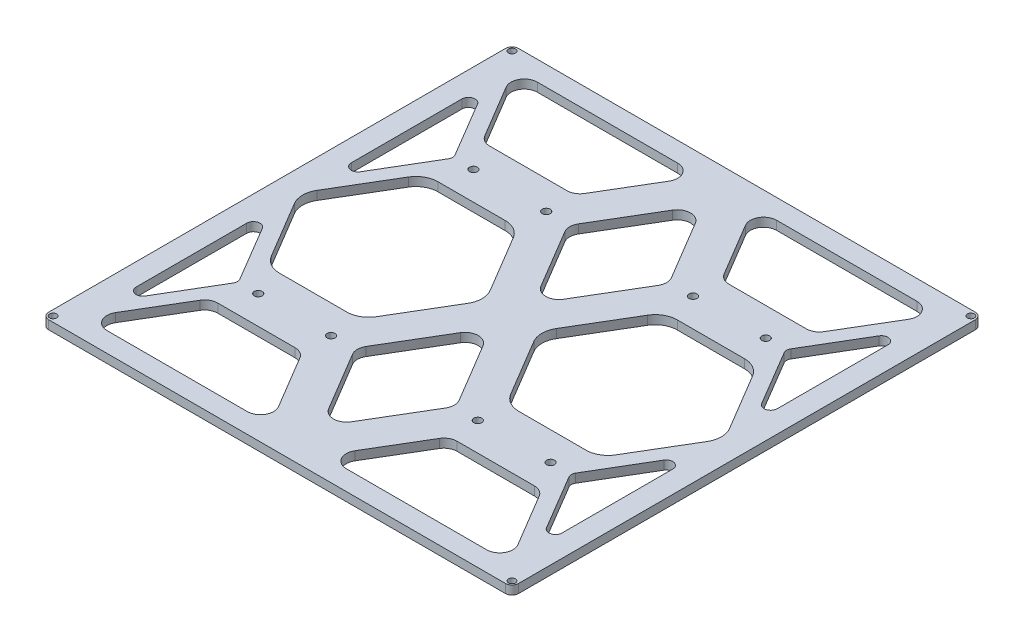
SolidWorks part; units mm, degrees
ref_plane "정면" through (0, 0, 0) normal (0, 0, 1) x (1, 0, 0)
ref_plane "윗면" through (0, 0, 0) normal (0, 1, 0) x (1, 0, 0)
ref_plane "우측면" through (0, 0, 0) normal (1, 0, 0) x (0, 0, -1)
sketch "스케치1" plane through (0, 0, 0) normal (0, 1, 0) x (1, 0, 0)
  line L1 (-107, -107) -> (107, -107)
  line L2 (-107, -107) -> (-107, 107)
  line L3 (-107, 107) -> (107, 107)
  line L4 (107, -107) -> (107, 107)
  line L5 (-107, -107) -> (107, 107) construction
  line L6 (-107, 107) -> (107, -107) construction
  point P0 (0, 0)
  dimension "D1" = 214
extrude "보스-돌출1" add sketch "스케치1" along normal blind 4
fillet "필렛1" radius 3 4 edges at (107, 2, -107) (107, 2, 107) (-107, 2, 107) (-107, 2, -107)
sketch "스케치2" plane through (0, 4, 0) normal (0, 1, 0) x (1, 0, 0)
  line L0 (0, 104.5) -> (0, -104.5) construction
  line L1 (-104.5, -104.5) -> (104.5, -104.5) construction
  line L2 (-104.5, -104.5) -> (-104.5, 104.5) construction
  line L3 (-104.5, 104.5) -> (104.5, 104.5) construction
  line L4 (104.5, -104.5) -> (104.5, 104.5) construction
  line L5 (-104.5, -104.5) -> (104.5, 104.5) construction
  line L6 (-104.5, 104.5) -> (104.5, -104.5) construction
  line L7 (33.425, -49) -> (-33.425, -49) construction
  line L8 (33.425, -49) -> (33.425, 49) construction
  line L9 (33.425, 49) -> (-33.425, 49) construction
  line L10 (-33.425, -49) -> (-33.425, 49) construction
  line L11 (33.425, -49) -> (-33.425, 49) construction
  line L12 (33.425, 49) -> (-33.425, -49) construction
  line L13 (-66.575, -49) -> (66.575, -49) construction
  line L14 (-66.575, -49) -> (-66.575, 49) construction
  line L15 (-66.575, 49) -> (66.575, 49) construction
  line L16 (66.575, -49) -> (66.575, 49) construction
  line L17 (-66.575, -49) -> (66.575, 49) construction
  line L18 (-66.575, 49) -> (66.575, -49) construction
  circle A0 centre (-104.5, 104.5) radius 1.6
  circle A1 centre (104.5, -104.5) radius 1.6
  circle A2 centre (-104.5, -104.5) radius 1.6
  circle A3 centre (104.5, 104.5) radius 1.6
  circle A4 centre (-66.575, 49) radius 1.8
  circle A5 centre (66.575, 49) radius 1.8
  circle A6 centre (-66.575, -49) radius 1.8
  circle A7 centre (66.575, -49) radius 1.8
  circle A8 centre (-33.425, 49) radius 1.8
  circle A9 centre (33.425, 49) radius 1.8
  circle A10 centre (-33.425, -49) radius 1.8
  circle A11 centre (33.425, -49) radius 1.8
  point P0 (0, 0)
  point P9 (0, 0)
  point P15 (0, 0)
  dimension "D2" = 3.2
  dimension "D6" = 3.6
  dimension "D7" = 3.6
  dimension "D1" = 209
  dimension "D3" = 98
  dimension "D4" = 66.85
  dimension "D5" = 33.15
extrude "컷-돌출1" cut sketch "스케치2" against normal through all
sketch "스케치3" plane through (0, 4, 0) normal (0, 1, 0) x (1, 0, 0)
  line L0 (0, 107) -> (0, -107) construction
  line L1 (104, 107) -> (-104, 107) construction
  line L2 (-104, -107) -> (104, -107) construction
  line L3 (-97, 98) -> (-12, 98)
  line L4 (97, 98) -> (12, 98)
  line L5 (-12, 98) -> (-33.5, 61.9202)
  line L6 (12, 98) -> (33.5, 61.9202)
  line L7 (-33.5, 61.9202) -> (-75.5, 61.9202)
  line L8 (33.5, 61.9202) -> (75.5, 61.9202)
  line L9 (-75.5, 61.9202) -> (-97, 98)
  line L10 (75.5, 61.9202) -> (97, 98)
  line L11 (-66.575, 49) -> (-66.575, 61.9202) construction
  line L12 (-66.575, 49) -> (-66.575, 36.0798) construction
  line L13 (-97, 85.1244) -> (-97, 12.8756)
  line L14 (-97, 12.8756) -> (-75.575, 49)
  line L15 (-75.575, 49) -> (-97, 85.1244)
  line L16 (97, 85.1244) -> (97, 12.8756)
  line L17 (-107, 0) -> (107, 0) construction
  line L18 (-107, 104) -> (-107, -104) construction
  line L19 (107, -104) -> (107, 104) construction
  line L20 (97, 12.8756) -> (75.575, 49)
  line L21 (75.575, 49) -> (97, 85.1244)
  line L22 (97, -85.1244) -> (97, -12.8756)
  line L23 (-75.5, -61.9202) -> (-97, -98)
  line L24 (-33.5, -61.9202) -> (-75.5, -61.9202)
  line L25 (-12, -98) -> (-33.5, -61.9202)
  line L26 (-97, -98) -> (-12, -98)
  line L27 (75.575, -49) -> (97, -85.1244)
  line L28 (97, -12.8756) -> (75.575, -49)
  line L29 (-97, -12.8756) -> (-75.575, -49)
  line L30 (75.5, -61.9202) -> (97, -98)
  line L31 (33.5, -61.9202) -> (75.5, -61.9202)
  line L32 (12, -98) -> (33.5, -61.9202)
  line L33 (97, -98) -> (12, -98)
  line L34 (-12, 0) -> (-33.5, 36.0798)
  line L35 (-12, 0) -> (-33.5, -36.0798)
  line L36 (-33.5, 36.0798) -> (-75.5, 36.0798)
  line L37 (-33.5, -36.0798) -> (-75.5, -36.0798)
  line L38 (-75.5, 36.0798) -> (-97, 0)
  line L39 (-75.5, -36.0798) -> (-97, 0)
  line L40 (75.5, 36.0798) -> (97, 0)
  line L41 (33.5, 36.0798) -> (75.5, 36.0798)
  line L42 (12, 0) -> (33.5, 36.0798)
  line L43 (75.5, -36.0798) -> (97, 0)
  line L44 (33.5, -36.0798) -> (75.5, -36.0798)
  line L45 (12, 0) -> (33.5, -36.0798)
  line L46 (0, 87) -> (-23.0357, 48.3431)
  line L47 (0, 87) -> (23.0357, 48.3431)
  line L48 (-23.0357, 48.3431) -> (0, 9.6862)
  line L49 (23.0357, 48.3431) -> (0, 9.6862)
  line L50 (-23.0357, -48.3431) -> (0, -9.6862)
  line L51 (0, -87) -> (-23.0357, -48.3431)
  line L52 (23.0357, -48.3431) -> (0, -9.6862)
  line L53 (0, -87) -> (23.0357, -48.3431)
  line L54 (-97, -85.1244) -> (-97, -12.8756)
  line L55 (-75.575, -49) -> (-97, -85.1244)
  dimension "D1" = 42
  dimension "D2" = 10
  dimension "D3" = 12
  dimension "D4" = 45
  dimension "D5" = 20
  dimension "D6" = 42
  dimension "D7" = 9
extrude "컷-돌출2" cut sketch "스케치3" against normal through all
fillet "필렛2" radius 10 12 edges at (-12, 2, 0) (-33.5, 2, 36.0798) (-97, 2, 0) (-75.5, 2, -36.0798) (-33.5, 2, -36.0798) (75.5, 2, -36.0798) (33.5, 2, -36.0798) (-75.5, 2, 36.0798) (12, 2, 0) (33.5, 2, 36.0798) (75.5, 2, 36.0798) (97, 2, 0)
fillet "필렛3" radius 6 16 edges at (97, 2, -98) (12, 2, -98) (-12, 2, -98) (-97, 2, -98) (75.5, 2, -61.9202) (33.5, 2, -61.9202) (-33.5, 2, -61.9202) (-75.5, 2, -61.9202) (12, 2, 98) (97, 2, 98) (33.5, 2, 61.9202) (75.5, 2, 61.9202) (-33.5, 2, 61.9202) (-12, 2, 98) (-97, 2, 98) (-75.5, 2, 61.9202)
fillet "필렛4" radius 3 12 edges at (97, 2, 12.8756) (-97, 2, 12.8756) (75.575, 2, 49) (-75.575, 2, 49) (-97, 2, 85.1244) (97, 2, 85.1244) (97, 2, -85.1244) (75.575, 2, -49) (97, 2, -12.8756) (-97, 2, -85.1244) (-97, 2, -12.8756) (-75.575, 2, -49)
fillet "필렛5" radius 6 8 edges at (0, 2, -87) (23.0357, 2, -48.3431) (-23.0357, 2, -48.3431) (0, 2, -9.6862) (0, 2, 87) (-23.0357, 2, 48.3431) (0, 2, 9.6862) (23.0357, 2, 48.3431)
